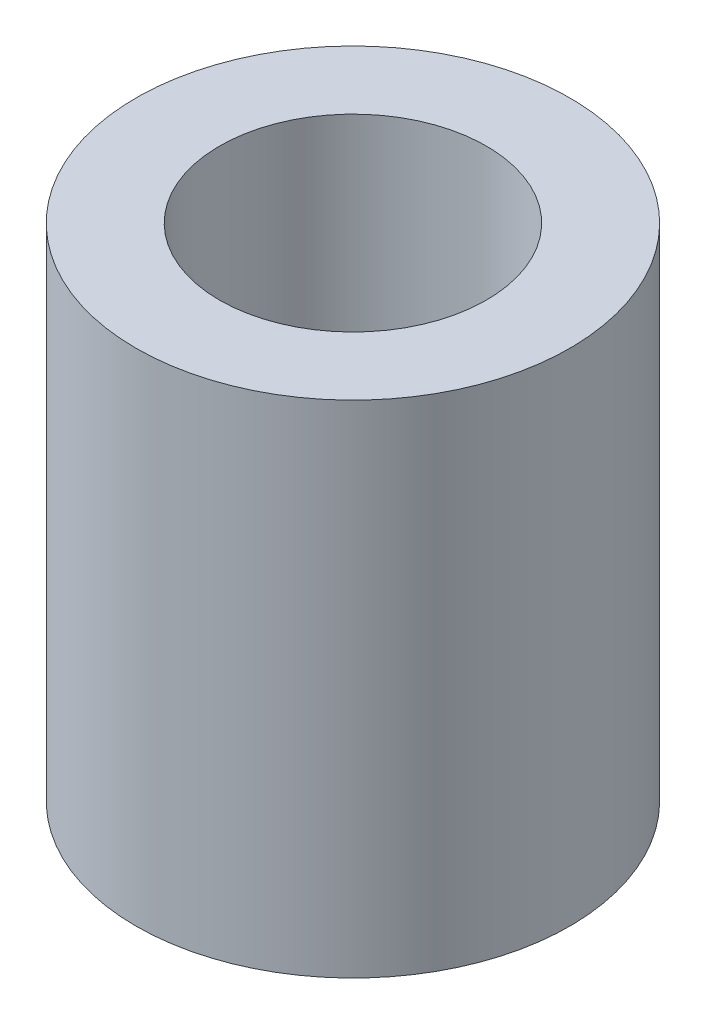
SolidWorks part; units mm, degrees
ref_plane "Front Plane" through (0, 0, 0) normal (0, 0, 1) x (1, 0, 0)
ref_plane "Top Plane" through (0, 0, 0) normal (0, 1, 0) x (1, 0, 0)
ref_plane "Right Plane" through (0, 0, 0) normal (1, 0, 0) x (0, 0, -1)
sketch "Sketch1" plane through (0, 0, 0) normal (0, 1, 0) x (1, 0, 0)
  circle A0 centre (0, 0) radius 4
  circle A1 centre (0, 0) radius 6.5
  dimension "D1" = 8
  dimension "D2" = 2.5
extrude "Boss-Extrude1" add sketch "Sketch1" along normal blind 15
